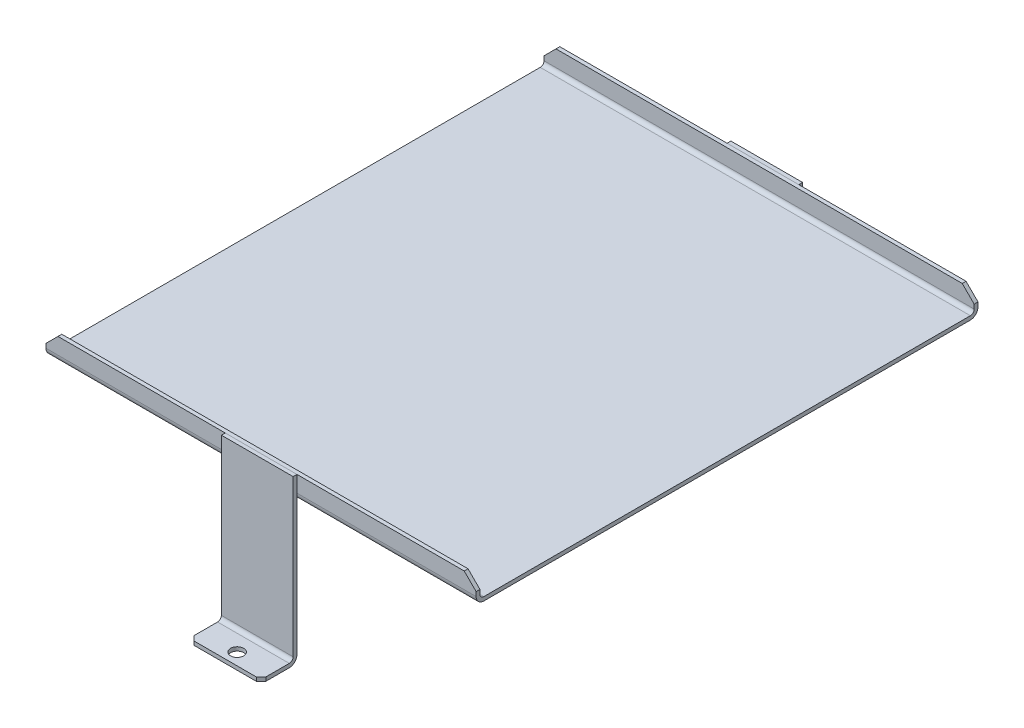
SolidWorks part; units mm, degrees
ref_plane "Front" through (0, 0, 0) normal (0, 0, 1) x (1, 0, 0)
ref_plane "Top" through (0, 0, 0) normal (0, 1, 0) x (1, 0, 0)
ref_plane "Right" through (0, 0, 0) normal (1, 0, 0) x (0, 0, -1)
sketch "Sketch1" plane through (0, 0, 0) normal (1, 0, 0) x (0, 0, -1)
  line L0 (0, 69.9751) -> (0, -17.0753) construction
  line L1 (-120, 0) -> (-105, 0)
  line L2 (-105, 0) -> (-105, 68.5)
  line L3 (-105, 68.5) -> (-106.6, 68.5)
  line L4 (-106.6, 68.5) -> (-106.6, 1.6)
  line L5 (-106.6, 1.6) -> (-120, 1.6)
  line L6 (-120, 1.6) -> (-120, 0)
  dimension "D1" = 1.6
  dimension "D2" = 1.6
  dimension "D3" = 15
  dimension "D4" = 68.5
  dimension "D5" = 105
extrude "Boss-Extrude1" add sketch "Sketch1" along normal mid plane 30
fillet "Fillet1" radius 1.6 1 edges at (0, 1.6, 106.6)
fillet "Fillet2" radius 3.2 1 edges at (0, 0, 105)
chamfer "Chamfer1" distance 2 angle 45 2 edges at (15, 0.8, 120) (-15, 0.8, 120)
sketch "Sketch2" plane through (0, 0, 0) normal (0, 0, 1) x (1, 0, 0)
  line L0 (-90, 58.5) -> (90, 58.5)
  line L1 (90, 58.5) -> (90, 68.5)
  line L2 (90, 68.5) -> (-90, 68.5)
  line L3 (-90, 68.5) -> (-90, 58.5)
  line L4 (15, 68.5) -> (-15, 68.5) construction
  line L6 (0, -10.5946) -> (0, 38.8177) construction
  dimension "D1" = 10
  dimension "D4" = 180
extrude "Cut-Extrude1" add sketch "Sketch2" along normal mid plane 210 separate body
shell "Shell1" thickness 1.6
fillet "Fillet3" radius 1.6 2 edges at (0, 60.1, 103.4) (0, 60.1, -103.4)
fillet "Fillet4" radius 3.2 2 edges at (0, 58.5, 105) (0, 58.5, -105)
mirror "MirrorSolid1" about plane through (0, 0, 0) normal (0, 0, 1) of bodies 101 102
chamfer "Chamfer2" distance 5 angle 45 4 edges at (-90, 68.5, -104.2) (-90, 68.5, 104.2) (90, 68.5, -104.2) (90, 68.5, 104.2)
hole_wizard "M5 Clearance Hole1" positions "Sketch3" profile "Sketch4" hole size "M5" standard "JIS" end condition through all
sketch "Sketch3" plane through (0, 1.6, 0) normal (0, 1, 0) x (-1, 0, 0)
  line L0 (-81.5802, 0) -> (68.3954, 0) construction
  line L2 (-15, 108.2) -> (-15, 118) construction
  point P0 (0, 115)
  point P1 (0, -115)
  dimension "D1" = 230
  dimension "D2" = 15
sketch "Sketch4" plane through (0, 1.6, 115) normal (1, 0, 0) x (0, 0, 1)
  line L0 (0, 0) -> (0, 1.6)
  line L1 (0, 1.6) -> (2.75, 1.6)
  line L2 (2.75, 1.6) -> (2.75, 0)
  line L5 (2.75, 0) -> (0, 0)
  line L11 (0, -6.35) -> (0, 107.95) construction
  dimension "通し穴の直径" = 5.5
  dimension "通し穴の深さ" = 1.6
